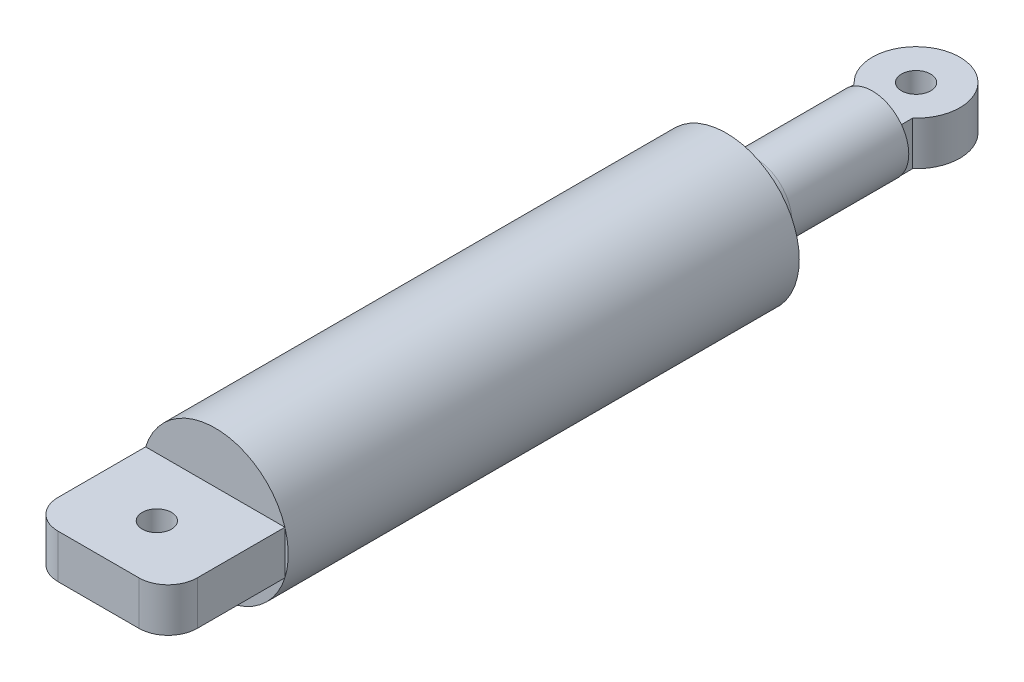
SolidWorks part; units mm, degrees
ref_plane "Front Plane" through (0, 0, 0) normal (0, 0, 1) x (1, 0, 0)
ref_plane "Top Plane" through (0, 0, 0) normal (0, 1, 0) x (1, 0, 0)
ref_plane "Right Plane" through (0, 0, 0) normal (1, 0, 0) x (0, 0, -1)
sketch "Sketch1" plane through (0, 0, 0) normal (0, 0, 1) x (1, 0, 0)
  circle A0 centre (0, 0) radius 5
  dimension "D1" = 10
extrude "Boss-Extrude1" add sketch "Sketch1" along normal blind 35
sketch "Sketch2" plane through (0, 0, 35) normal (0, 0, 1) x (1, 0, 0)
  line L1 (-4.7697, 1.5) -> (4.7697, 1.5)
  line L2 (-4.7697, 1.5) -> (-4.7697, -1.5)
  line L3 (-4.7697, -1.5) -> (4.7697, -1.5)
  line L4 (4.7697, 1.5) -> (4.7697, -1.5)
  line L5 (-4.7697, 1.5) -> (4.7697, -1.5) construction
  line L6 (-4.7697, -1.5) -> (4.7697, 1.5) construction
  circle A0 centre (0, 0) radius 5 construction
  point P0 (0, 0)
  dimension "D1" = 3
extrude "Boss-Extrude2" add sketch "Sketch2" along normal blind 8
sketch "Sketch3" plane through (0, 0, 0) normal (0, 0, -1) x (-1, 0, 0)
  circle A0 centre (0, 0) radius 2.5
  dimension "D1" = 5
extrude "Boss-Extrude3" add sketch "Sketch3" along normal blind 10
sketch "Sketch4" plane through (0, 0, -10) normal (0, 0, -1) x (-1, 0, 0)
  line L1 (-2, 1.5) -> (2, 1.5)
  line L2 (-2, 1.5) -> (-2, -1.5)
  line L3 (-2, -1.5) -> (2, -1.5)
  line L4 (2, 1.5) -> (2, -1.5)
  line L5 (-2, 1.5) -> (2, -1.5) construction
  line L6 (-2, -1.5) -> (2, 1.5) construction
  circle A0 centre (0, 0) radius 2.5 construction
  point P0 (0, 0)
  dimension "D1" = 4
extrude "Boss-Extrude4" add sketch "Sketch4" along normal blind 3
sketch "Sketch5" plane through (0, -1.5, 0) normal (0, -1, 0) x (-1, 0, 0)
  line L0 (-2, 13) -> (2, 13) construction
  circle A0 centre (0, 13) radius 3
  dimension "D1" = 6
extrude "Boss-Extrude5" add sketch "Sketch5" against normal blind 3
fillet "Fillet1" radius 2 2 edges at (4.7697, 0, 43) (-4.7697, 0, 43)
fillet "Fillet4" radius 2 1 edges at (-2.5, 0, 0)
sketch "Sketch6" plane through (0, 1.5, 0) normal (0, 1, 0) x (1, 0, 0)
  line L0 (-3, 13) -> (3, 13) construction
  arc A0 (2, 10.7639) -> (-2, 10.7639) centre (0, 13) ccw construction
  circle A1 centre (0, 13) radius 1
  dimension "D1" = 2
extrude "Cut-Extrude1" cut sketch "Sketch6" against normal through all
sketch "Sketch7" plane through (0, 1.5, 0) normal (0, 1, 0) x (1, 0, 0)
  line L0 (0, -43) -> (0, -35)
  line L2 (2.7697, -43) -> (-2.7697, -43) construction
  line L3 (4.7697, -35) -> (-4.7697, -35) construction
  circle A0 centre (0, -39) radius 1
  dimension "D1" = 2
extrude "Cut-Extrude2" cut sketch "Sketch7" against normal through all contours A0
